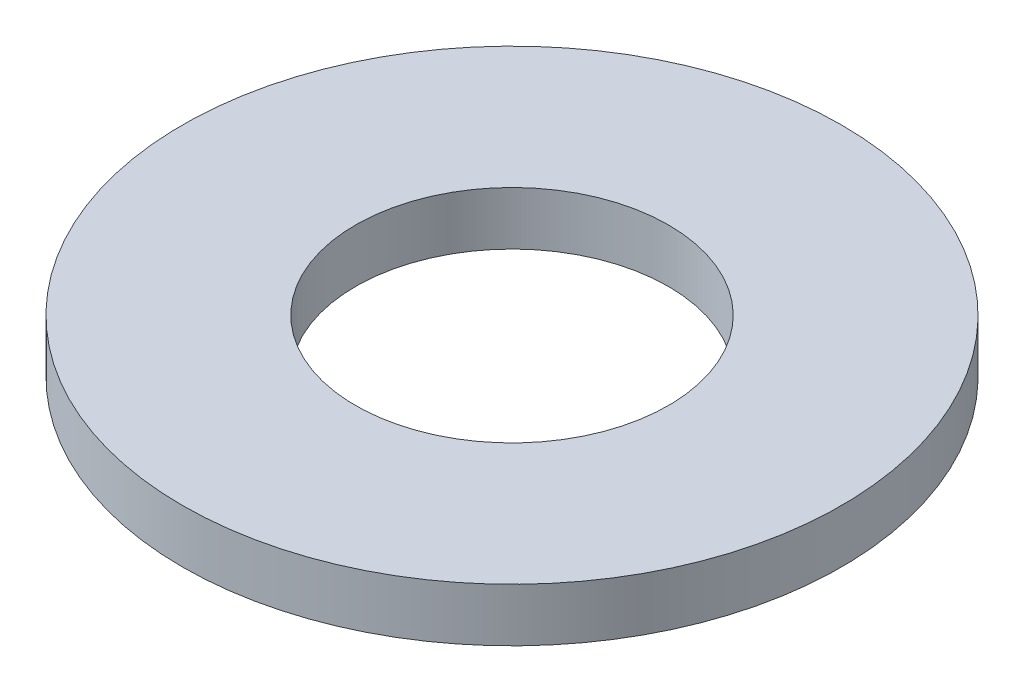
SolidWorks part; units mm, degrees
ref_plane "Front Plane" through (0, 0, 0) normal (0, 0, 1) x (1, 0, 0)
ref_plane "Top Plane" through (0, 0, 0) normal (0, 1, 0) x (1, 0, 0)
ref_plane "Right Plane" through (0, 0, 0) normal (1, 0, 0) x (0, 0, -1)
sketch "Sketch1" plane through (0, 0, 0) normal (0, 1, 0) x (1, 0, 0)
  circle A0 centre (0, 0) radius 12.36
  dimension "D1" = 24.72
extrude "Boss-Extrude1" add sketch "Sketch1" along normal blind 2
sketch "Sketch2" plane through (0, 0, 0) normal (0, -1, 0) x (-1, 0, 0)
  circle A0 centre (0, 0) radius 5.8674
  dimension "D1" = 11.7348
extrude "Cut-Extrude1" cut sketch "Sketch2" against normal through all
sketch "Sketch4" plane through (0, 2, 0) normal (0, 1, 0) x (1, 0, 0)
  circle A0 centre (0, 0) radius 12.0429 construction
  text T0 "<b>1mm</b>" font "Cambria" height 5.08
extrude "Cut-Extrude2" [suppressed] cut sketch "Sketch4" against normal blind 0.2
